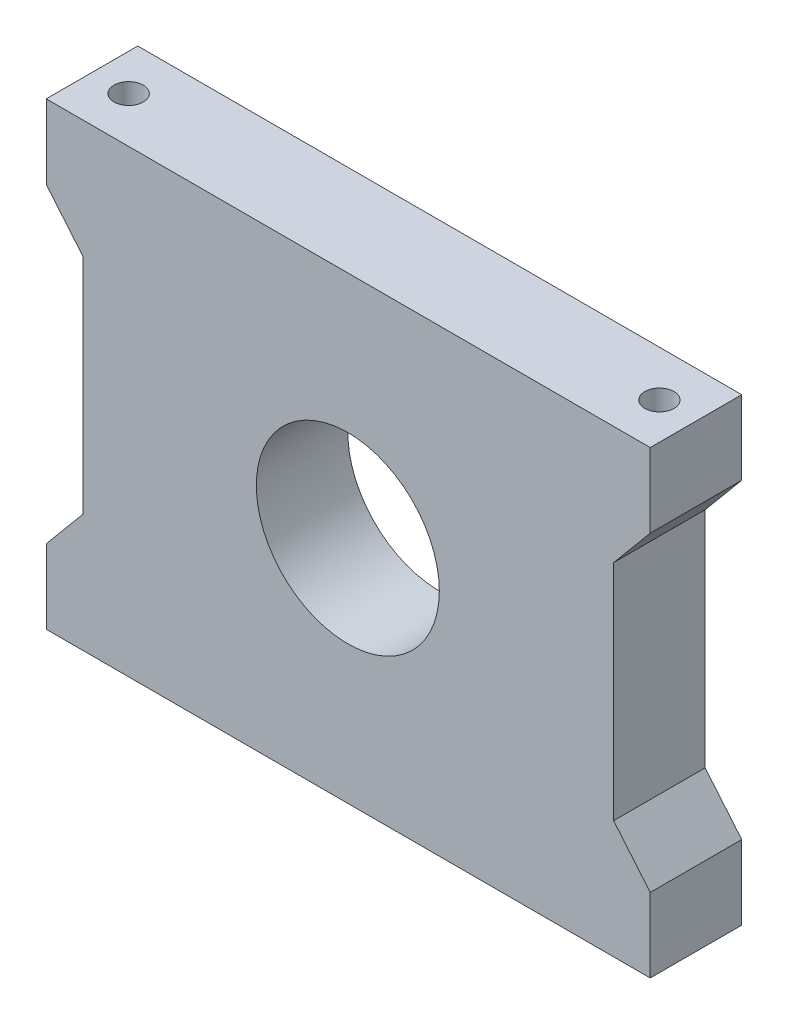
SolidWorks part; units mm, degrees
material "ABS"
ref_plane "Płaszczyzna przednia" through (0, 0, 0) normal (0, 0, 1) x (1, 0, 0)
ref_plane "Płaszczyzna górna" through (0, 0, 0) normal (0, 1, 0) x (1, 0, 0)
ref_plane "Płaszczyzna prawa" through (0, 0, 0) normal (1, 0, 0) x (0, 0, -1)
sketch "Szkic1" plane through (0, 0, 0) normal (0, 0, 1) x (1, 0, 0)
  line L0 (0, 0) -> (66, 0)
  line L1 (0, 0) -> (0, 50.2) construction
  line L3 (66, 50.2) -> (0, 50.2)
  line L4 (66, 0) -> (66, 8.1)
  line L5 (66, 8.1) -> (62, 12.8869)
  line L6 (62, 12.8869) -> (62, 37.3131)
  line L7 (0, 25.1) -> (37.9059, 25.1) construction
  line L8 (33, 1.7581) -> (33, 11.1868) construction
  line L9 (32.9524, 8.1) -> (50032.9524, 8.1) construction
  line L10 (32.9524, 15.1) -> (33, 8.1) construction
  line L11 (66, 42.1) -> (62, 37.3131)
  line L12 (66, 50.2) -> (66, 42.1)
  line L13 (0, 50.2) -> (0, 42.1)
  line L14 (0, 42.1) -> (4, 37.3131)
  line L15 (4, 12.8869) -> (4, 37.3131)
  line L16 (0, 8.1) -> (4, 12.8869)
  line L17 (0, 0) -> (0, 8.1)
  circle A1 centre (32.9524, 25.1) radius 10
  point P19 (62, 25.1)
  dimension "D3" = 20
  dimension "D2" = 66
  dimension "D4" = 4
  dimension "D5" = 7
extrude "Dodanie-wyciągnięcie1" add sketch "Szkic1" along normal blind 10
sketch "Szkic2" plane through (0, 50.2, 0) normal (0, 1, 0) x (1, 0, 0)
  line L0 (33, 0) -> (33, -10) construction
  line L1 (66, 0) -> (0, 0) construction
  line L2 (66, -10) -> (0, -10) construction
  line L3 (4, -5) -> (62, -5) construction
  circle A0 centre (4, -5) radius 1.6
  circle A1 centre (62, -5) radius 1.6
  point P9 (33, -5)
  dimension "D2" = 3.2
  dimension "D1" = 58
extrude "Wytnij-wyciągnięcie1" cut sketch "Szkic2" against normal blind 10
ref_plane "Płaszczyzna2" through (0, 25.1, 0) normal (0, 1, 0) x (1, 0, 0)
mirror "Lustro1" about plane through (0, 25.1, 0) normal (0, 1, 0) of "Wytnij-wyciągnięcie1"
